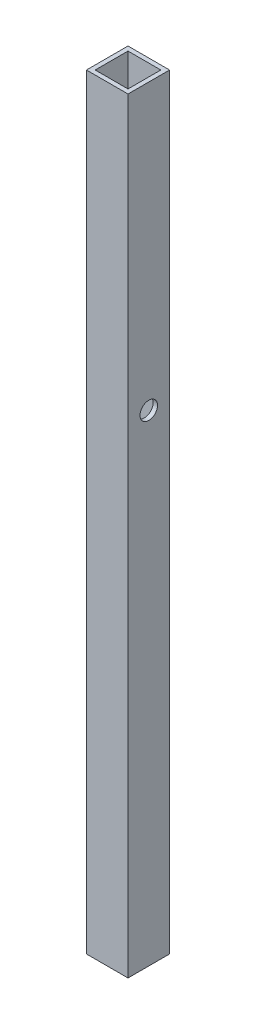
SolidWorks part; units mm, degrees
ref_plane "Front Plane" through (0, 0, 0) normal (0, 0, 1) x (1, 0, 0)
ref_plane "Top Plane" through (0, 0, 0) normal (0, 1, 0) x (1, 0, 0)
ref_plane "Right Plane" through (0, 0, 0) normal (1, 0, 0) x (0, 0, -1)
sketch "Sketch1" plane through (0, 0, 0) normal (0, 1, 0) x (1, 0, 0)
  line L1 (-9.5, -9.5) -> (9.5, -9.5)
  line L2 (-9.5, -9.5) -> (-9.5, 9.5)
  line L3 (-9.5, 9.5) -> (9.5, 9.5)
  line L4 (9.5, -9.5) -> (9.5, 9.5)
  line L5 (-9.5, -9.5) -> (9.5, 9.5) construction
  line L6 (-9.5, 9.5) -> (9.5, -9.5) construction
  point P0 (0, 0)
  dimension "D1" = 19
  dimension "D2" = 19
extrude "Extrude-Thin1" add sketch "Sketch1" along normal blind 350 thin thin type one direction reverse wall 2
sketch "Sketch2" plane through (9.5, 0, 0) normal (1, 0, 0) x (0, 0, -1)
  line L0 (-9.5, 0) -> (9.5, 0) construction
  circle A0 centre (0, 220) radius 4
  dimension "D1" = 8
  dimension "D2" = 220
extrude "Cut-Extrude1" cut sketch "Sketch2" against normal blind 4
